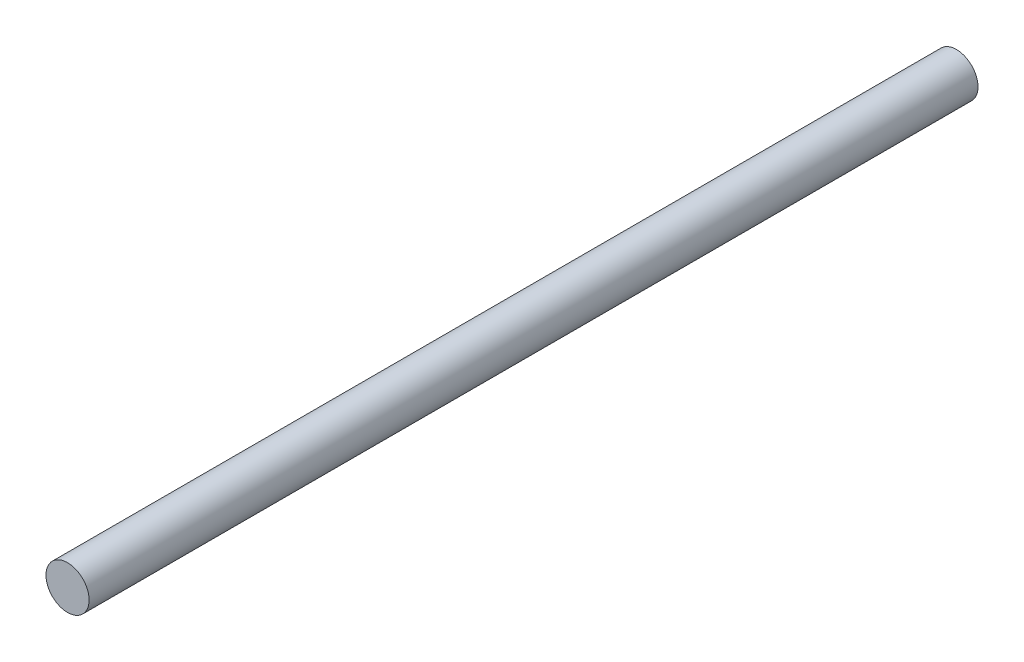
SolidWorks part; units mm, degrees
material "6061-T6 (SS)"
ref_plane "Front Plane" through (0, 0, 0) normal (0, 0, 1) x (1, 0, 0)
ref_plane "Top Plane" through (0, 0, 0) normal (0, 1, 0) x (1, 0, 0)
ref_plane "Right Plane" through (0, 0, 0) normal (1, 0, 0) x (0, 0, -1)
sketch "Body sketch" plane through (0, 0, 0) normal (0, 0, 1) x (1, 0, 0)
  circle A0 centre (0, 0) radius 2.5
extrude "Body" add sketch "Body sketch" along normal blind 103
